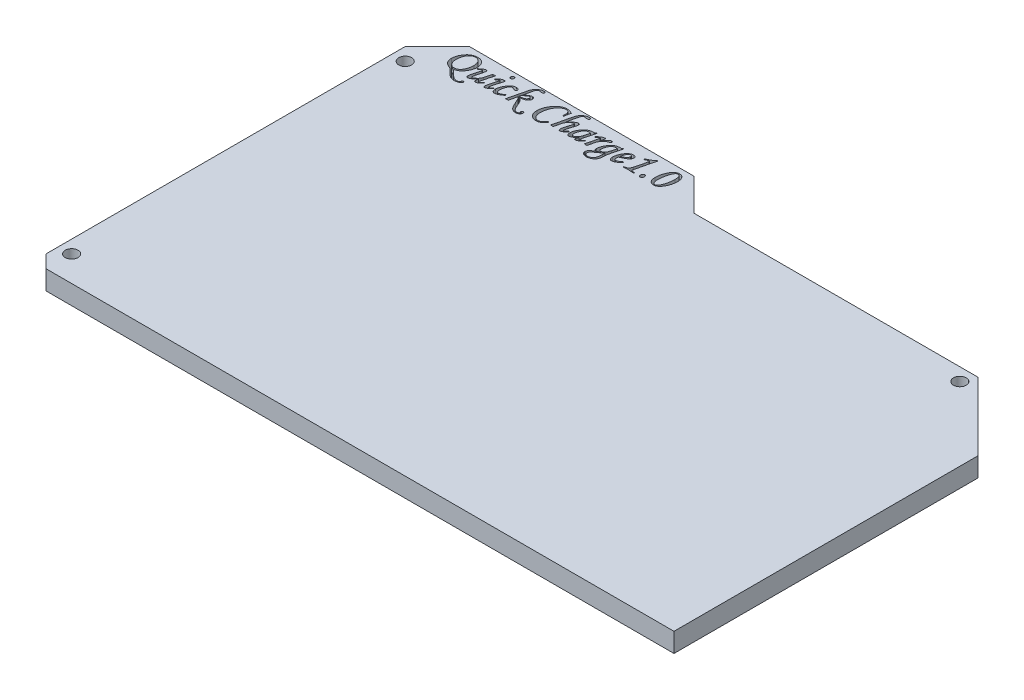
SolidWorks part; units mm, degrees
ref_plane "前视基准面" through (0, 0, 0) normal (0, 0, 1) x (1, 0, 0)
ref_plane "上视基准面" through (0, 0, 0) normal (0, 1, 0) x (1, 0, 0)
ref_plane "右视基准面" through (0, 0, 0) normal (1, 0, 0) x (0, 0, -1)
sketch "草图1" plane through (0, 0, 0) normal (0, 1, 0) x (1, 0, 0)
  line L1 (0, 0) -> (84, 0)
  line L2 (0, 0) -> (0, -50)
  line L3 (0, -50) -> (84, -50)
  line L4 (84, 0) -> (84, -50)
  dimension "D1" = 84
  dimension "D2" = 50
extrude "凸台-拉伸1" add sketch "草图1" along normal blind 3
sketch "草图2" plane through (0, 0, 0) normal (0, 1, 0) x (1, 0, 0)
  line L0 (0, 0) -> (0, 8)
  line L1 (5, 13) -> (40, 13)
  line L2 (40, 13) -> (45, 8)
  line L3 (45, 8) -> (89.2934, 8)
  line L4 (89.2934, 8) -> (99.9, -2.6066)
  line L6 (99.9, -2.6066) -> (99.9, -50)
  line L7 (99.9, -50) -> (84, -50)
  line L8 (84, 0) -> (0, 0) construction
  line L9 (5, 13) -> (0, 8)
  line L16 (0, 0) -> (0, -50)
  line L17 (0, -50) -> (84, -50)
  line L18 (84, -50) -> (84, 0)
  line L19 (84, 0) -> (0, 0)
  line L22 (84, -50) -> (84, 0)
  line L23 (84, 0) -> (0, 0)
  dimension "D1" = 45
  dimension "D2" = 45
  dimension "D3" = 15.9
  dimension "D4" = 8
  dimension "D5" = 5
  dimension "D6" = 35
  dimension "D7" = 15
  dimension "D8" = 0
extrude "凸台-拉伸2" add sketch "草图2" along normal blind 3
hole_wizard "大小mm 暗销孔1" positions "草图4" profile "草图3" hole size "Ø2.0" standard "GB" end condition through all
sketch "草图4" plane through (0, 3, 0) normal (0, 1, 0) x (1, 0, 0)
  line L0 (0, 8) -> (0, -50) construction
  line L2 (0, -50) -> (99.9, -50) construction
  line L4 (89.2934, 8) -> (45, 8) construction
  line L5 (99.9, -2.6066) -> (89.2934, 8) construction
  point P0 (2, 6)
  point P2 (2, -46)
  point P4 (88.465, 6)
  dimension "D1" = 2
  dimension "D2" = 2
  dimension "D3" = 4
  dimension "D5" = 2
  dimension "D6" = 2
sketch "草图3" plane through (2, 3, -6) normal (1, 0, 0) x (0, 0, 1)
  line L0 (0, 0) -> (0, 3)
  line L1 (0, 3) -> (1, 3)
  line L2 (1, 3) -> (1, 0)
  line L5 (1, 0) -> (0, 0)
  line L11 (0, -6.35) -> (0, 107.95) construction
  dimension "通孔孔直径" = 2
  dimension "通孔孔深度" = 3
sketch "草图6" plane through (0, 3, 0) normal (0, 1, 0) x (1, 0, 0)
  text T0 "Quick Charge1.0" font "华文隶书" height 3.5
extrude "切除-拉伸1" cut sketch "草图6" against normal blind 3
chamfer "倒角1" distance 2 angle 45 1 edges at (0, 1.5, 50)
